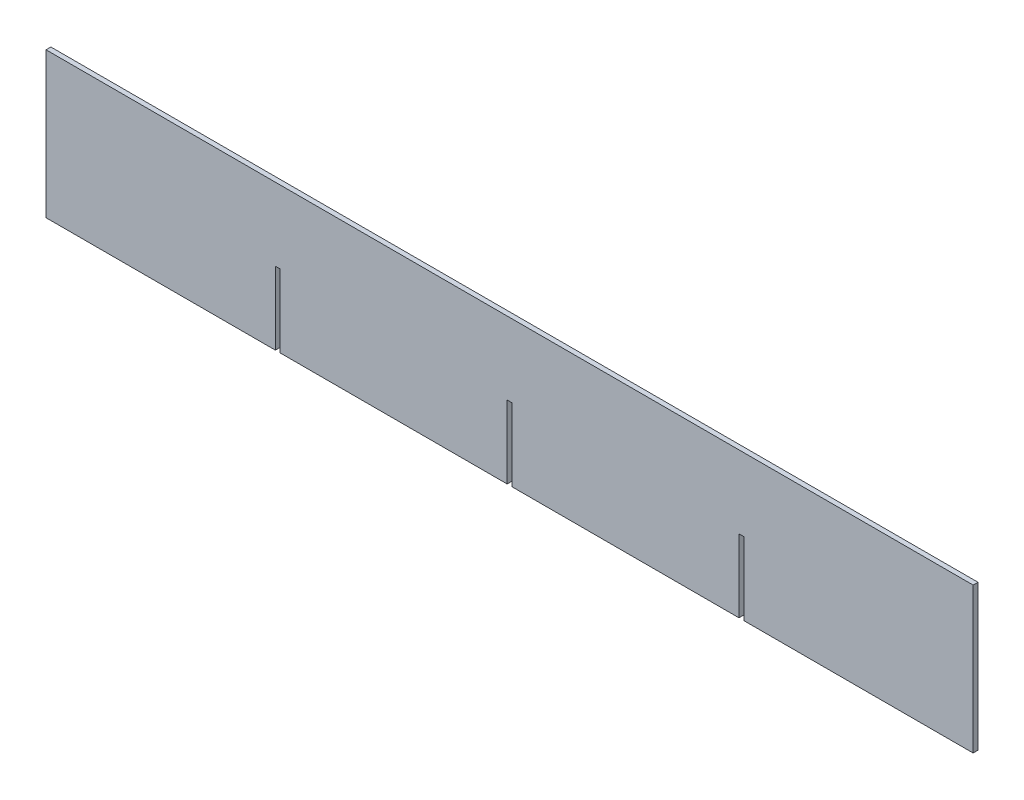
SolidWorks part; units mm, degrees
material "Mahogany"
ref_plane "Front Plane" through (0, 0, 0) normal (0, 0, 1) x (1, 0, 0)
ref_plane "Top Plane" through (0, 0, 0) normal (0, 1, 0) x (1, 0, 0)
ref_plane "Right Plane" through (0, 0, 0) normal (1, 0, 0) x (0, 0, -1)
sketch "Sketch1" plane through (0, 0, 0) normal (0, 0, 1) x (1, 0, 0)
  line L0 (-119.5, -37.5) -> (-119.5, 37.5) construction
  line L1 (-239, -37.5) -> (239, -37.5) construction
  line L2 (-239, -37.5) -> (-239, 37.5) construction
  line L3 (-239, 37.5) -> (239, 37.5) construction
  line L4 (239, -37.5) -> (239, 37.5) construction
  line L5 (-239, -37.5) -> (239, 37.5) construction
  line L6 (-239, 37.5) -> (239, -37.5) construction
  line L7 (0, -37.5) -> (0, 37.5) construction
  line L8 (119.5, -37.5) -> (119.5, 37.5) construction
  line L10 (-1.25, -37.5) -> (-1.25, 0)
  line L11 (-120.75, -37.5) -> (-118.25, -37.5) construction
  line L12 (-120.75, -37.5) -> (-120.75, 0)
  line L13 (-120.75, 0) -> (-118.25, 0)
  line L14 (-118.25, -37.5) -> (-118.25, 0)
  line L15 (-120.75, -37.5) -> (-118.25, 0) construction
  line L16 (-120.75, 0) -> (-118.25, -37.5) construction
  line L17 (-1.25, 0) -> (1.25, 0)
  line L18 (1.25, -37.5) -> (1.25, 0)
  line L19 (118.25, -37.5) -> (118.25, 0)
  line L20 (118.25, 0) -> (120.75, 0)
  line L21 (120.75, -37.5) -> (120.75, 0)
  line L25 (-120.75, -37.5) -> (-239, -37.5)
  line L26 (-239, -37.5) -> (-239, 37.5)
  line L27 (-239, 37.5) -> (239, 37.5)
  line L28 (239, 37.5) -> (239, -37.5)
  line L29 (239, -37.5) -> (120.75, -37.5)
  line L31 (118.25, -37.5) -> (1.25, -37.5)
  line L32 (-1.25, -37.5) -> (-118.25, -37.5)
  point P0 (0, 0)
  point P8 (-119.5, -18.75)
  point P19 (-119.5, 0)
  point P20 (0, 0)
  dimension "D1" = 478
  dimension "D2" = 75
  dimension "D3" = 119.5
  dimension "D4" = 3
  dimension "D5" = 119.5
  dimension "D6" = 2.5
  dimension "D7" = 3
extrude "Boss-Extrude1" add sketch "Sketch1" along normal mid plane 2.5
